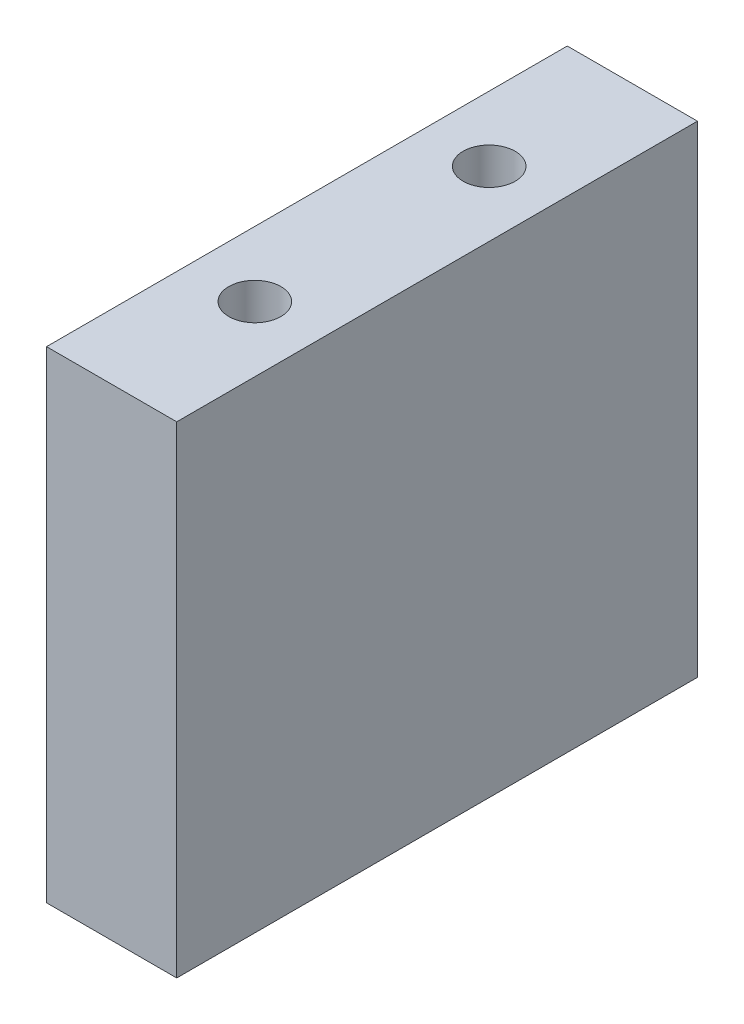
SolidWorks part; units mm, degrees
ref_plane "Alzado" through (0, 0, 0) normal (0, 0, 1) x (1, 0, 0)
ref_plane "Planta" through (0, 0, 0) normal (0, 1, 0) x (1, 0, 0)
ref_plane "Vista lateral" through (0, 0, 0) normal (1, 0, 0) x (0, 0, -1)
sketch "Croquis1" plane through (0, 0, 0) normal (1, 0, 0) x (0, 0, -1)
  line L1 (-40, 37) -> (40, 37)
  line L2 (-40, 37) -> (-40, -37)
  line L3 (-40, -37) -> (40, -37)
  line L4 (40, 37) -> (40, -37)
  line L5 (-40, 37) -> (40, -37) construction
  line L6 (-40, -37) -> (40, 37) construction
  point P0 (0, 0)
  dimension "D1" = 80
  dimension "D2" = 74
extrude "Saliente-Extruir1" add sketch "Croquis1" against normal blind 20
sketch "Croquis3" plane through (0, 37, 0) normal (0, 1, 0) x (1, 0, 0)
  circle A0 centre (-10, -18) radius 4
  circle A1 centre (-10, 18) radius 4
  dimension "D1" = 8
  dimension "D2" = 8
extrude "Cortar-Extruir2" cut sketch "Croquis3" against normal blind 25
sketch "Croquis4" plane through (0, -37, 0) normal (0, -1, 0) x (1, 0, 0)
  line L0 (0, 40) -> (0, -40) construction
  circle A0 centre (-10, 30) radius 4
  circle A1 centre (-10, -30) radius 4
  dimension "D1" = 30
  dimension "D3" = 10
  dimension "D4" = 10
  dimension "D5" = 8
  dimension "D6" = 8
  dimension "D2" = 30
extrude "Cortar-Extruir3" cut sketch "Croquis4" against normal blind 30
